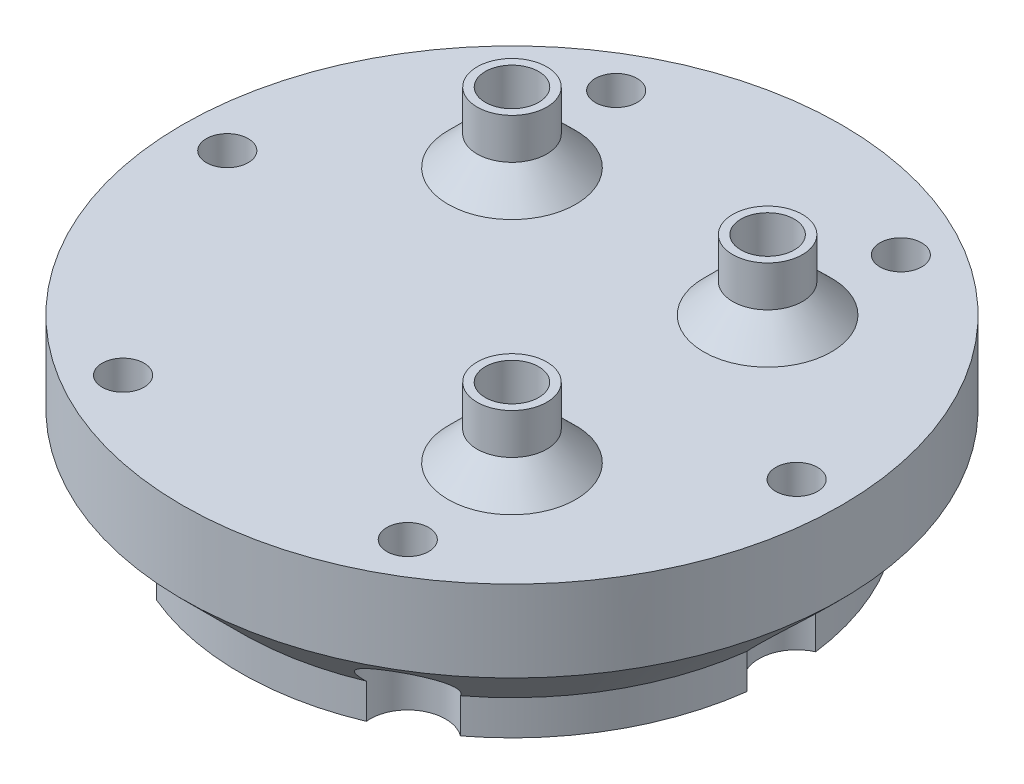
SolidWorks part; units mm, degrees
ref_plane "Front Plane" through (0, 0, 0) normal (0, 0, 1) x (1, 0, 0)
ref_plane "Top Plane" through (0, 0, 0) normal (0, 1, 0) x (1, 0, 0)
ref_plane "Right Plane" through (0, 0, 0) normal (1, 0, 0) x (0, 0, -1)
sketch "Sketch3" plane through (0, 0, 0) normal (0, 0, 1) x (1, 0, 0)
  line L0 (0, 0) -> (0, 34.9563) construction
  line L1 (0, 0) -> (23.365, 0)
  line L2 (23.365, 0) -> (23.365, 3)
  line L3 (23.365, 3) -> (28.365, 8)
  line L4 (28.365, 8) -> (28.365, 15)
  line L5 (28.365, 15) -> (0, 15)
  line L6 (0, 0) -> (0, 15)
  dimension "D1" = 56.73
  dimension "D2" = 5
  dimension "D3" = 45
  dimension "D4" = 7
  dimension "D5" = 3
revolve "Revolve1" add sketch "Sketch3" angle 360 about L0
hole_wizard "CBORE for M3 Hex Socket Head Cap Screw1" positions "Sketch5" profile "Sketch6" counterbore size "M3" standard "DIN" end condition through all
sketch "Sketch5" plane through (0, 0, 0) normal (0, -1, 0) x (-1, 0, 0)
  line L0 (0, 0) -> (12.25, 21.2176) construction
  line L2 (0, 0) -> (0, 24.5) construction
  line L4 (0, 0) -> (-12.25, 21.2176) construction
  line L6 (0, 0) -> (-12.25, -21.2176) construction
  line L8 (0, 0) -> (12.25, -21.2176) construction
  line L10 (0, 0) -> (24.5, 0) construction
  line L12 (0, 0) -> (-24.5, 0) construction
  circle A0 centre (0, 0) radius 24.5
  point P6 (12.25, 21.2176)
  point P15 (-12.25, 21.2176)
  point P19 (-12.25, -21.2176)
  point P24 (12.25, -21.2176)
  point P28 (24.5, 0)
  point P33 (-24.5, 0)
  dimension "D1" = 49
  dimension "D2" = 30
sketch "Sketch6" plane through (24.5, 0, 0) normal (1, 0, 0) x (0, 0, -1)
  line L0 (0, 0) -> (0, 15)
  line L1 (0, 15) -> (1.8, 15)
  line L3 (1.8, 15) -> (1.8, 10.4)
  line L4 (1.8, 10.4) -> (3.25, 10.4)
  line L5 (3.25, 10.4) -> (3.25, 0)
  line L7 (3.25, 0) -> (0, 0)
  line L11 (0, -6.35) -> (0, 107.95) construction
  dimension "Thru Hole Dia." = 3.6
  dimension "Thru Hole Depth" = 15
  dimension "C'Bore Dia." = 6.5
  dimension "C'Bore Depth" = 10.4
hole_wizard "HoleWzd2" positions "Sketch7" profile "Sketch8" legacy
sketch "Sketch7" plane through (0, 0, 0) normal (0, -1, 0) x (-1, 0, 0)
  circle A0 centre (0, 0) radius 12.8
  point P6 (0, 12.8)
  point P8 (12.8, 0)
  point P10 (0, -12.8)
  point P12 (-12.8, 0)
  dimension "D1" = 25.6
sketch "Sketch8" plane through (12.8, 0, 0) normal (1, 0, 0) x (0, 0, -1)
  line L0 (0, 0) -> (0, 9.3)
  line L1 (0, 9.3) -> (2.3, 7)
  line L2 (2.3, 7) -> (2.3, 0)
  line L4 (2.3, 0) -> (0, 0)
  line L6 (0, 9.3) -> (-2.3, 7) construction
  line L7 (0, -4.2442) -> (0, 117.3081) construction
  dimension "Diameter" = 4.6
  dimension "Depth" = 7
  dimension "Drill Angle" = 90
sketch "Sketch9" plane through (0, 15, 0) normal (0, 1, 0) x (1, 0, 0)
  line L1 (-11, -11) -> (11, -11)
  line L2 (-11, -11) -> (-11, 11)
  line L3 (-11, 11) -> (11, 11)
  line L4 (11, -11) -> (11, 11)
  line L5 (-11, -11) -> (11, 11) construction
  line L6 (-11, 11) -> (11, -11) construction
  circle A0 centre (-11, 11) radius 3
  circle A1 centre (11, 11) radius 3
  circle A2 centre (11, -11) radius 3
  circle A3 centre (-11, -11) radius 3
  point P0 (0, 0)
  dimension "D2" = 6
  dimension "D3" = 2
  dimension "D4" = 2
  dimension "D1" = 22
extrude "Boss-Extrude1" add sketch "Sketch9" along normal blind 6 contours A0 | A1 | A2
hole_wizard "HoleWzd1" positions "Sketch10" profile "Sketch11" legacy
sketch "Sketch10" plane through (0, 21, 0) normal (0, 1, 0) x (1, 0, 0)
  point P0 (11, -11)
  point P3 (11, 11)
  point P6 (-11, 11)
sketch "Sketch11" plane through (11, 21, 11) normal (1, 0, 0) x (0, 0, 1)
  line L0 (0, 0) -> (0, 7)
  line L1 (0, 7) -> (2.3, 7)
  line L2 (2.3, 7) -> (2.3, 0)
  line L3 (2.3, 0) -> (0, 0)
  line L4 (0, 110) -> (0, -10) construction
  dimension "Diameter" = 4.6
  dimension "Depth" = 7
chamfer "Chamfer1" distance 2.5 angle 45 3 edges at (11, 15, 14) (11, 15, -8) (-11, 15, -8)
